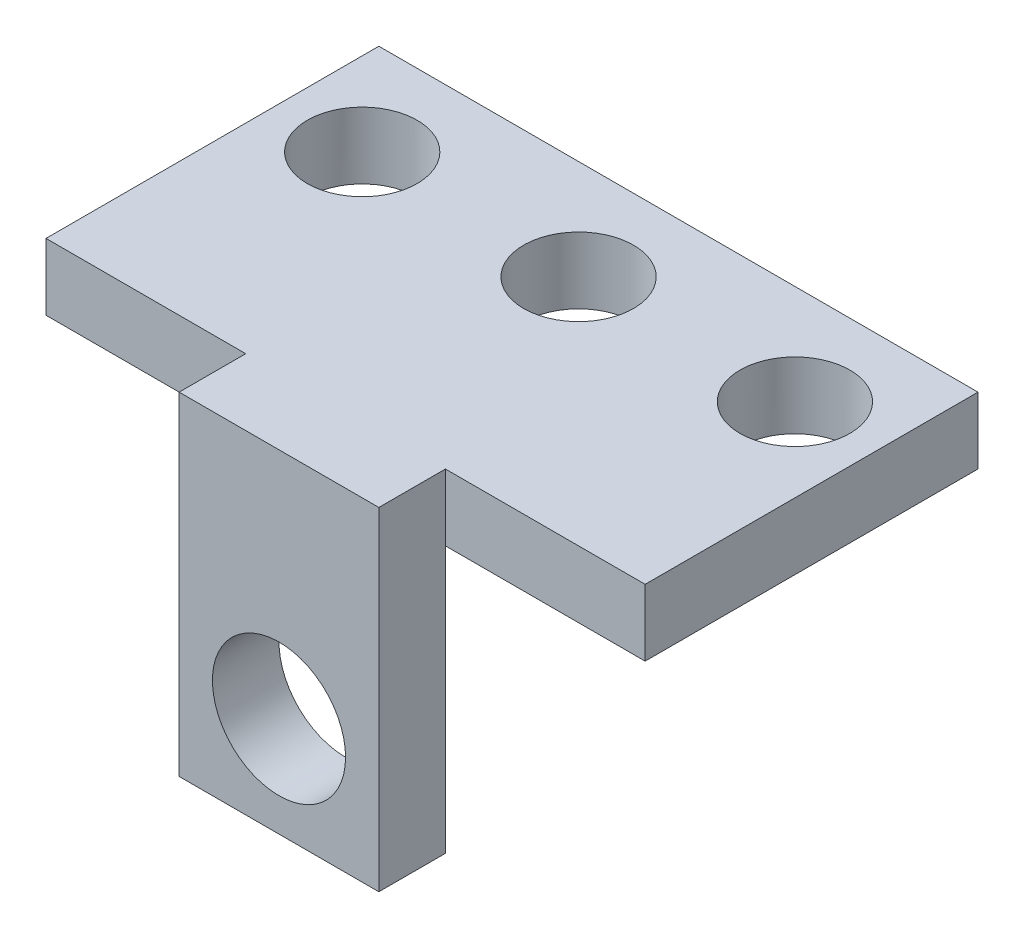
SolidWorks part; units mm, degrees
ref_plane "前视基准面" through (0, 0, 0) normal (0, 0, 1) x (1, 0, 0)
ref_plane "上视基准面" through (0, 0, 0) normal (0, 1, 0) x (1, 0, 0)
ref_plane "右视基准面" through (0, 0, 0) normal (1, 0, 0) x (0, 0, -1)
sketch "草图1" plane through (0, 0, 0) normal (0, 0, 1) x (1, 0, 0)
  line L1 (-3, -3) -> (3, -3)
  line L2 (-3, -3) -> (-3, 5)
  line L3 (-3, 5) -> (3, 5)
  line L4 (3, -3) -> (3, 5)
  circle A0 centre (0, 0) radius 2
  point P0 (0, 0)
  dimension "D3" = 4
  dimension "D4" = 3
  dimension "D1" = 6
  dimension "D2" = 8
extrude "凸台-拉伸1" add sketch "草图1" along normal blind 2
sketch "草图2" plane through (0, 5, 0) normal (0, 1, 0) x (1, 0, 0)
  line L0 (3, -2) -> (3, 10)
  line L1 (3, -2) -> (-3, -2)
  line L2 (-3, -2) -> (-3, 10)
  line L3 (-3, 10) -> (3, 10)
  line L4 (0, 10) -> (0, 7) construction
  circle A0 centre (0, 7) radius 1.65
  dimension "D3" = 3.3
  dimension "D1" = 12
  dimension "D2" = 3
extrude "凸台-拉伸2" add sketch "草图2" along normal blind 2
sketch "草图3" plane through (-3, 0, 0) normal (-1, 0, 0) x (0, 0, 1)
  line L6 (-10, 7) -> (0, 7)
  line L7 (-10, 7) -> (-10, 5)
  line L8 (-10, 5) -> (0, 5)
  line L9 (0, 7) -> (0, 5)
extrude "凸台-拉伸3" add sketch "草图3" along normal blind 6
sketch "草图4" plane through (3, 0, 0) normal (1, 0, 0) x (0, 0, -1)
  line L5 (-2, 7) -> (10, 7) construction
  line L6 (10, 5) -> (0, 5)
  line L7 (10, 5) -> (10, 7)
  line L8 (10, 7) -> (0, 7)
  line L9 (0, 5) -> (0, 7)
extrude "凸台-拉伸4" add sketch "草图4" along normal blind 6
sketch "草图6" plane through (0, 7, 0) normal (0, 1, 0) x (1, 0, 0)
  line L0 (-9, 0) -> (-9, 10) construction
  line L1 (9, 10) -> (9, 0) construction
  circle A0 centre (-6.5, 7) radius 1.65
  circle A1 centre (6.5, 7) radius 1.65
  dimension "D1" = 2.5
  dimension "D3" = 3.3
  dimension "D4" = 3.3
  dimension "D2" = 2.5
extrude "切除-拉伸1" cut sketch "草图6" against normal blind 6
